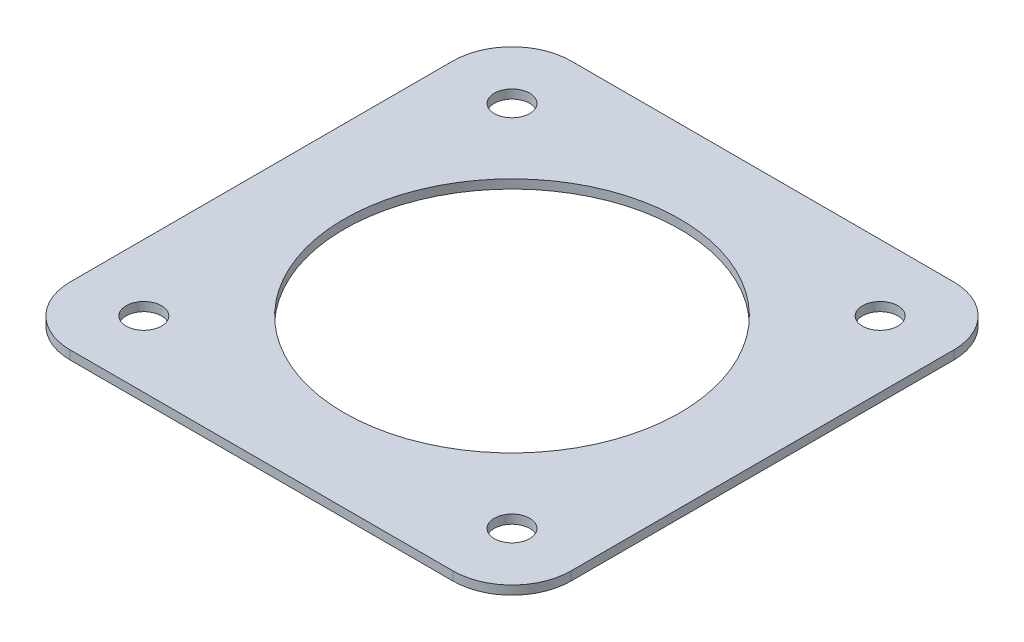
SolidWorks part; units mm, degrees
material "Гофрированная бумага"
ref_plane "Спереди" through (0, 0, 0) normal (0, 0, 1) x (1, 0, 0)
ref_plane "Сверху" through (0, 0, 0) normal (0, 1, 0) x (1, 0, 0)
ref_plane "Справа" through (0, 0, 0) normal (1, 0, 0) x (0, 0, -1)
sketch "Эскиз1" plane through (0, 0, 0) normal (0, 1, 0) x (1, 0, 0)
  line L1 (65, -85) -> (-65, -85)
  line L2 (85, -65) -> (85, 65)
  line L3 (65, 85) -> (-65, 85)
  line L4 (-85, -65) -> (-85, 65)
  line L5 (85, -85) -> (-85, 85) construction
  line L6 (85, 85) -> (-85, -85) construction
  arc A0 (-85, -65) -> (-65, -85) centre (-65, -65) ccw
  arc A1 (65, -85) -> (85, -65) centre (65, -65) ccw
  arc A2 (85, 65) -> (65, 85) centre (65, 65) ccw
  arc A3 (-65, 85) -> (-85, 65) centre (-65, 65) ccw
  circle A4 centre (-62.5, -62.5) radius 6
  circle A5 centre (-62.5, 62.5) radius 6
  circle A6 centre (62.5, 62.5) radius 6
  circle A7 centre (62.5, -62.5) radius 6
  circle A8 centre (0, 0) radius 57
  point P0 (0, 0)
  point P29 (0, 0)
  dimension "D2" = 20
  dimension "D3" = 12
  dimension "D6" = 114
  dimension "D1" = 170
  dimension "D4" = 62.5
  dimension "D5" = 4
extrude "Бобышка-Вытянуть1" add sketch "Эскиз1" along normal blind 3
